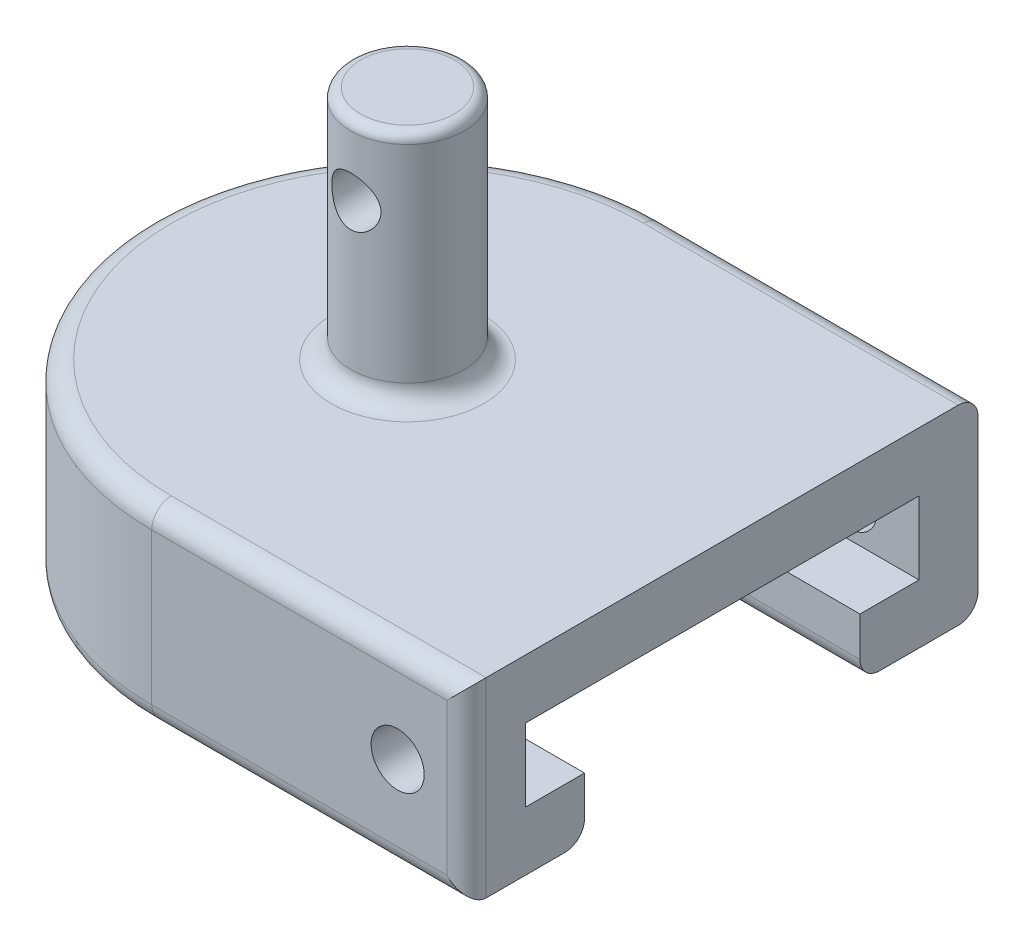
SolidWorks part; units mm, degrees
ref_plane "Front Plane" through (0, 0, 0) normal (0, 0, 1) x (1, 0, 0)
ref_plane "Top Plane" through (0, 0, 0) normal (0, 1, 0) x (1, 0, 0)
ref_plane "Right Plane" through (0, 0, 0) normal (1, 0, 0) x (0, 0, -1)
sketch "Sketch1" plane through (0, 0, 0) normal (0, 1, 0) x (1, 0, 0)
  line L0 (0, 13) -> (16, 13)
  line L1 (0, -13) -> (16, -13)
  line L2 (0, 7) -> (16, 7)
  line L3 (16, 13) -> (16, 7)
  line L4 (0, -7) -> (16, -7)
  line L5 (16, -7) -> (16, -13)
  arc A0 (0, 7) -> (0, -7) centre (0, 0) ccw
  arc A1 (0, 13) -> (0, -13) centre (0, 0) ccw
  dimension "D1" = 6
  dimension "D2" = 7
  dimension "D3" = 16
  dimension "D4" = 16
extrude "Boss-Extrude1" add sketch "Sketch1" along normal blind 3
sketch "Sketch2" plane through (0, 3, 0) normal (0, 1, 0) x (1, 0, 0)
  line L0 (0, 13) -> (16, 13)
  line L1 (16, 13) -> (16, 10)
  line L2 (16, 7) -> (16, 13) construction
  line L3 (16, -13) -> (0, -13)
  line L4 (16, -13) -> (16, -10)
  line L7 (16, -13) -> (16, -7) construction
  line L8 (0, 10) -> (16, 10)
  line L9 (0, -10) -> (16, -10)
  arc A0 (0, 10) -> (0, -10) centre (0, 0) ccw
  arc A1 (0, 13) -> (0, -13) centre (0, 0) ccw
  dimension "D2" = 3
extrude "Boss-Extrude2" add sketch "Sketch2" along normal blind 3.7
sketch "Sketch3" plane through (0, 6.7, 0) normal (0, 1, 0) x (1, 0, 0)
  line L0 (16, 13) -> (0, 13)
  line L1 (16, 13) -> (16, 7)
  line L3 (0, -13) -> (16, -13)
  line L4 (16, -13) -> (16, -7)
  line L5 (16, -7) -> (0, -7) construction
  line L6 (16, -10) -> (16, -7) construction
  line L8 (16, 7) -> (16, -7)
  arc A1 (0, 13) -> (0, -13) centre (0, 0) ccw
extrude "Boss-Extrude3" add sketch "Sketch3" along normal blind 3
sketch "Sketch4" plane through (0, 9.7, 0) normal (0, 1, 0) x (1, 0, 0)
  circle A0 centre (0, 0) radius 2.88
  dimension "D1" = 5.76
extrude "Boss-Extrude4" add sketch "Sketch4" along normal blind 12
hole_wizard "Ø2.5mm Dowel Hole1" positions "3DSketch4" profile "Sketch7" hole size "Ø2.5" standard "ANSI Metric" end condition through all
sketch3d "3DSketch4"
  point P0 (-0.0024, 18.1049, 2.88)
  point P12 (-0.0024, 18.1049, 2.88)
  point P15 (-0.0024, 18.1049, 2.88)
sketch "Sketch7" plane through (-0.0024, 18.1049, 2.88) normal (0, 1, 0) x (1, 0, 0.0008)
  line L0 (0, 0) -> (0, 15.8935)
  line L1 (0, 15.8935) -> (1.25, 15.8935)
  line L2 (1.25, 15.8935) -> (1.25, 0)
  line L5 (1.25, 0) -> (0, 0)
  line L11 (0, -6.35) -> (0, 107.95) construction
  dimension "Thru Hole Dia." = 2.5
  dimension "Thru Hole Depth" = 15.8935
sketch "Sketch8" plane through (0, 0, 13) normal (0, 0, 1) x (1, 0, 0)
  line L0 (16, 4.85) -> (0, 4.85) construction
  line L1 (16, 9.7) -> (16, 0) construction
  line L2 (0, 9.7) -> (0, 0) construction
  circle A0 centre (12.5, 4.85) radius 1.35
  dimension "D1" = 2.7
  dimension "D2" = 3.5
extrude "Cut-Extrude1" cut sketch "Sketch8" against normal through all
fillet "Fillet1" radius 1 10 edges at (8, 9.7, -13) (-13, 9.7, 0) (8, 0, -13) (-13, 0, 0) (8, 9.7, 13) (16, 4.85, 13) (8, 0, 13) (8, 0, -7) (-7, 0, 0) (8, 0, 7)
fillet "Fillet2" radius 1 1 edges at (0, 9.7, 2.88)
fillet "Fillet3" radius 0.5 1 edges at (0, 21.7, 2.88)
